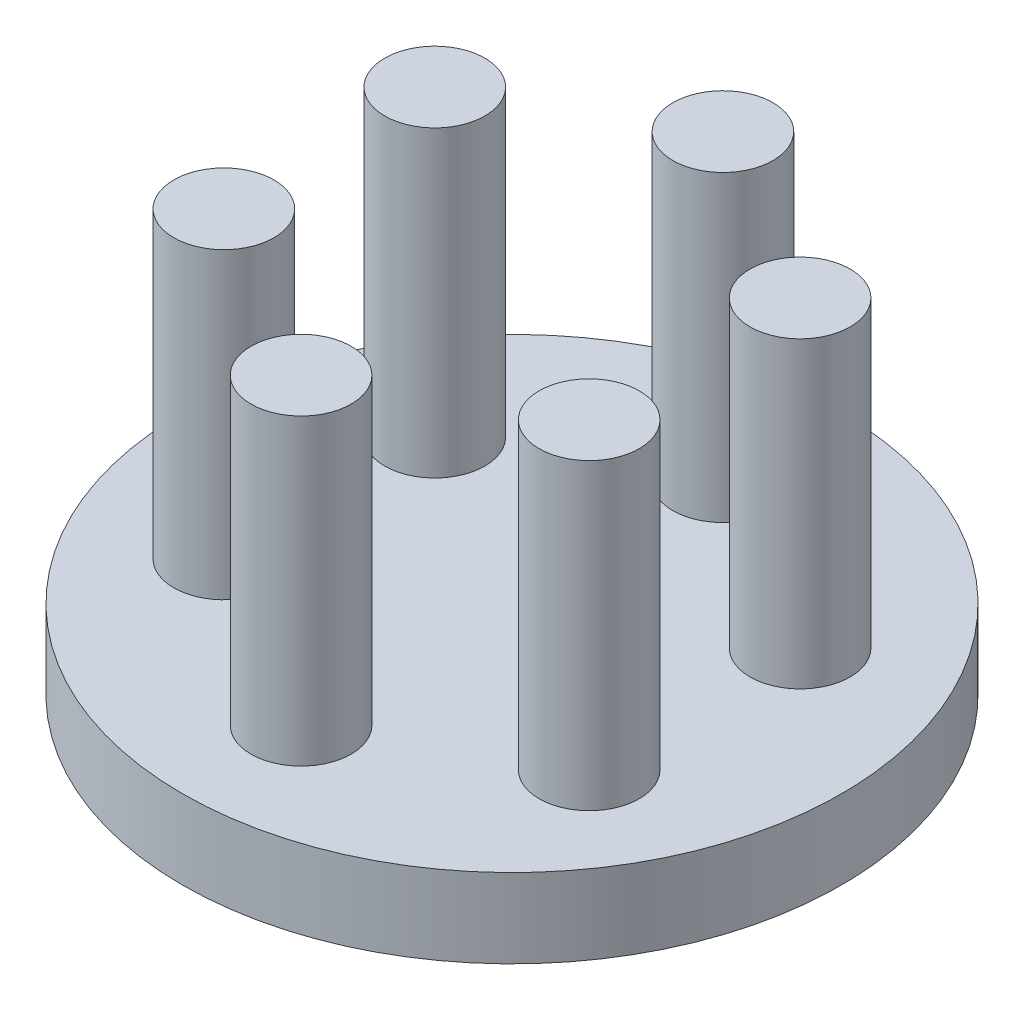
SolidWorks part; units mm, degrees
ref_plane "前视基准面" through (0, 0, 0) normal (0, 0, 1) x (1, 0, 0)
ref_plane "上视基准面" through (0, 0, 0) normal (0, 1, 0) x (1, 0, 0)
ref_plane "右视基准面" through (0, 0, 0) normal (1, 0, 0) x (0, 0, -1)
other "Configuration Table"
sketch "草图2" plane through (0, 0, 0) normal (0, 1, 0) x (1, 0, 0)
  line L0 (-12.5, 12.5) -> (12.5, -12.5) construction
  line L1 (-12.5, 12.5) -> (12.5, 12.5) construction
  line L2 (-12.5, 12.5) -> (-12.5, -12.5) construction
  line L3 (-12.5, -12.5) -> (12.5, -12.5) construction
  line L4 (12.5, 12.5) -> (12.5, -12.5) construction
  circle A0 centre (0, 0) radius 12.5
  point P4 (0, 0)
  dimension "D1" = 25
  dimension "D2" = 25
extrude "凸台-拉伸1" add sketch "草图2" along normal blind 3
sketch "草图3" plane through (0, 3, 0) normal (0, 1, 0) x (1, 0, 0)
  line L0 (0, 0) -> (16.3, 0) construction
  line L1 (0, 0) -> (0, 13.6059) construction
  line L2 (0, 0) -> (0, 8) construction
  line L3 (0, 8) -> (6.9282, 4) construction
  line L4 (6.9282, 4) -> (0, 0) construction
  line L5 (0, 0) -> (6.9282, -4) construction
  line L6 (6.9282, -4) -> (6.9282, 4) construction
  line L7 (6.9282, -4) -> (0, -8) construction
  line L8 (0, -8) -> (0, 0) construction
  line L9 (0, 0) -> (-6.9282, -4) construction
  line L10 (-6.9282, -4) -> (0, -8) construction
  line L11 (0, 0) -> (-6.9282, 4) construction
  line L12 (-6.9282, 4) -> (-6.9282, -4) construction
  circle A0 centre (0, 8) radius 1.9
  circle A1 centre (6.9282, 4) radius 1.9
  circle A2 centre (6.9282, -4) radius 1.9
  circle A3 centre (0, -8) radius 1.9
  circle A4 centre (-6.9282, -4) radius 1.9
  circle A5 centre (-6.9282, 4) radius 1.9
  dimension "D2" = 3.8
  dimension "D4" = 3.8
  dimension "D5" = 8
  dimension "D1" = 8
  dimension "D3" = 8
extrude "凸台-拉伸2" add sketch "草图3" along normal blind 11.5
